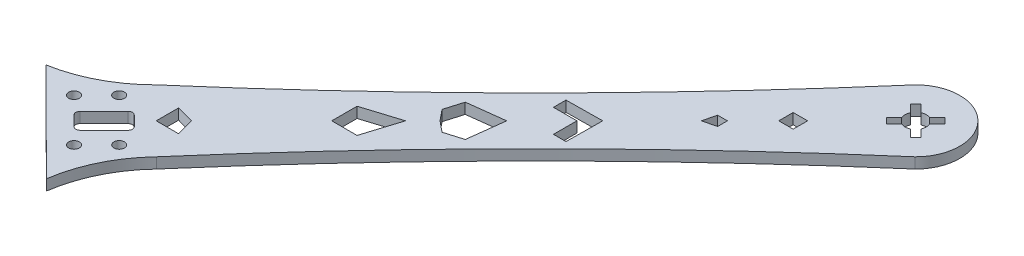
SolidWorks part; units mm, degrees
ref_plane "Front Plane" through (0, 0, 0) normal (0, 0, 1) x (1, 0, 0)
ref_plane "Top Plane" through (0, 0, 0) normal (0, 1, 0) x (1, 0, 0)
ref_plane "Right Plane" through (0, 0, 0) normal (1, 0, 0) x (0, 0, -1)
sketch "Sketch1" plane through (0, 0, 0) normal (0, 1, 0) x (1, 0, 0)
  line L10 (60.0917, 64.6321) -> (55.2292, 69.4947)
  line L16 (52.4008, 69.4947) -> (41.0871, 58.181)
  line L17 (48.778, 50.49) -> (60.0917, 61.8037)
  line L18 (41.0871, 55.3525) -> (45.9496, 50.49)
  line L19 (14.2058, 69.0753) -> (60.6011, 22.8579)
  line L20 (43.5183, 52.9213) -> (234.2901, 243.693) construction
  line L21 (243.1498, 255.0983) -> (246.6853, 258.6339)
  line L22 (246.6853, 258.6339) -> (249.2309, 256.0883)
  line L23 (77.4168, 57.5604) -> (77.473, 57.6166)
  line L24 (245.6954, 252.5527) -> (249.2309, 256.0883)
  line L25 (245.6954, 248.5013) -> (249.2309, 244.9658)
  line L26 (249.2309, 244.9658) -> (246.6853, 242.4202)
  line L27 (243.1498, 245.9558) -> (246.6853, 242.4202)
  line L28 (239.0984, 245.9558) -> (235.5629, 242.4202)
  line L29 (235.5629, 242.4202) -> (233.0173, 244.9658)
  line L30 (236.5528, 248.5013) -> (233.0173, 244.9658)
  line L31 (236.5528, 252.5527) -> (233.0173, 256.0883)
  line L32 (233.0173, 256.0883) -> (235.5629, 258.6339)
  line L33 (239.0984, 255.0983) -> (235.5629, 258.6339)
  line L34 (62.8152, 72.2182) -> (62.8152, 82.7618)
  line L38 (104.0283, 113.4313) -> (104.0283, 125.3044)
  line L41 (150.5809, 170.9817) -> (161.5788, 170.9817)
  line L46 (208.9653, 218.3682) -> (208.9653, 225.1401)
  line L50 (196.9239, 206.3268) -> (192.3102, 206.3268)
  line L53 (150.5809, 176.8608) -> (150.5809, 170.9817)
  line L57 (104.0283, 125.3044) -> (104.0283, 113.4313)
  line L61 (215.7796, 225.1825) -> (208.9653, 225.1401)
  line L65 (167.6611, 177.064) -> (150.5809, 176.8608)
  line L67 (145.105, 154.5079) -> (127.7745, 152.3696)
  line L68 (127.7745, 152.3696) -> (125.2805, 143.9595)
  line L69 (121.3701, 130.773) -> (104.0283, 125.3044)
  line L72 (125.2805, 143.9595) -> (129.4431, 138.846)
  line L73 (71.0727, 80.4757) -> (62.8152, 82.7618)
  line L75 (192.3102, 206.3268) -> (190.8032, 200.2062)
  line L77 (71.0727, 80.4757) -> (73.3588, 72.2182)
  line L78 (62.8152, 72.2182) -> (73.3588, 72.2182)
  line L81 (104.0283, 113.4313) -> (115.9014, 113.4313)
  line L82 (121.3701, 130.773) -> (115.9014, 113.4313)
  line L85 (134.5566, 134.6834) -> (129.4431, 138.846)
  line L86 (142.9667, 137.1774) -> (134.5566, 134.6834)
  line L87 (145.105, 154.5079) -> (142.9667, 137.1774)
  line L91 (161.5788, 159.9839) -> (161.5788, 170.9817)
  line L92 (167.4579, 159.9839) -> (161.5788, 159.9839)
  line L93 (167.6611, 177.064) -> (167.4579, 159.9839)
  line L96 (196.9239, 201.7132) -> (190.8032, 200.2062)
  line L97 (196.9239, 206.3268) -> (196.9239, 201.7132)
  line L98 (208.9653, 218.3682) -> (215.7371, 218.3682)
  line L99 (215.7796, 225.1825) -> (215.7371, 218.3682)
  arc A13 (14.2058, 69.0753) -> (48.1574, 86.8197) centre (3.0711, 131.7332) ccw
  arc A17 (77.473, 57.6166) -> (60.6011, 22.8579) centre (123.5868, 13.7587) ccw
  arc A18 (55.2292, 69.4947) -> (52.4008, 69.4947) centre (53.815, 68.0805) ccw
  arc A19 (60.0917, 61.8037) -> (60.0917, 64.6321) centre (58.6775, 63.2179) ccw
  arc A20 (41.0871, 58.181) -> (41.0871, 55.3525) centre (42.5013, 56.7668) ccw
  arc A21 (45.9496, 50.49) -> (48.778, 50.49) centre (47.3638, 51.9042) ccw
  circle A22 centre (43.7049, 73.9479) radius 2.5
  circle A23 centre (33.0983, 63.3413) radius 2.5
  circle A24 centre (53.3185, 43.1212) radius 2.5
  circle A25 centre (63.9251, 53.7278) radius 2.5
  arc A26 (255.6504, 235.7939) -> (226.391, 265.0533) centre (241.1241, 250.527) ccw
  arc A27 (48.1574, 86.8197) -> (226.391, 265.0533) centre (-1066.7439, 1379.9546) ccw
  arc A28 (77.4168, 57.5604) -> (255.6504, 235.7939) centre (1370.5517, -1057.341) cw
  arc A29 (236.5528, 252.5527) -> (236.5528, 248.5013) centre (241.1241, 250.527) ccw
  arc A30 (239.0984, 245.9558) -> (243.1498, 245.9558) centre (241.1241, 250.527) ccw
  arc A31 (245.6954, 248.5013) -> (239.0984, 255.0983) centre (241.1241, 250.527) ccw
  point P7 (57.6605, 67.0634)
  point P41 (247.9581, 257.3611)
  point P57 (241.1241, 250.527)
  dimension "D2" = 5
  dimension "D3" = 20
  dimension "D4" = 10
  dimension "D5" = 5
  dimension "D1" = 5
  dimension "D6" = 1.8
extrude "Boss-Extrude2" add sketch "Sketch1" against normal blind 5
sketch "Sketch2" plane through (0, 0, 0) normal (0, 1, 0) x (1, 0, 0)
  line L2 (77.473, 57.6166) -> (77.4168, 57.5604)
  line L3 (14.2058, 69.0753) -> (60.6011, 22.8579)
  line L4 (77.473, 57.6166) -> (77.4168, 57.5604)
  line L5 (14.2058, 69.0753) -> (60.6011, 22.8579)
  circle A0 centre (63.9251, 53.7278) radius 2.5 construction
  circle A1 centre (63.9251, 53.7278) radius 2.5
  arc A5 (255.6504, 235.7939) -> (77.4168, 57.5604) centre (1370.5517, -1057.341) ccw
  arc A6 (255.6504, 235.7939) -> (226.391, 265.0533) centre (241.1241, 250.527) ccw
  arc A7 (48.1574, 86.8197) -> (226.391, 265.0533) centre (-1066.7439, 1379.9546) ccw
  arc A8 (14.2058, 69.0753) -> (48.1574, 86.8197) centre (3.0711, 131.7332) ccw
  arc A9 (77.473, 57.6166) -> (60.6011, 22.8579) centre (123.5868, 13.7587) ccw
  arc A10 (255.6504, 235.7939) -> (77.4168, 57.5604) centre (1370.5517, -1057.341) ccw
  arc A11 (255.6504, 235.7939) -> (226.391, 265.0533) centre (241.1241, 250.527) ccw
  arc A12 (48.1574, 86.8197) -> (226.391, 265.0533) centre (-1066.7439, 1379.9546) ccw
  arc A13 (14.2058, 69.0753) -> (48.1574, 86.8197) centre (3.0711, 131.7332) ccw
  arc A14 (77.473, 57.6166) -> (60.6011, 22.8579) centre (123.5868, 13.7587) ccw
  dimension "D1" = 0
